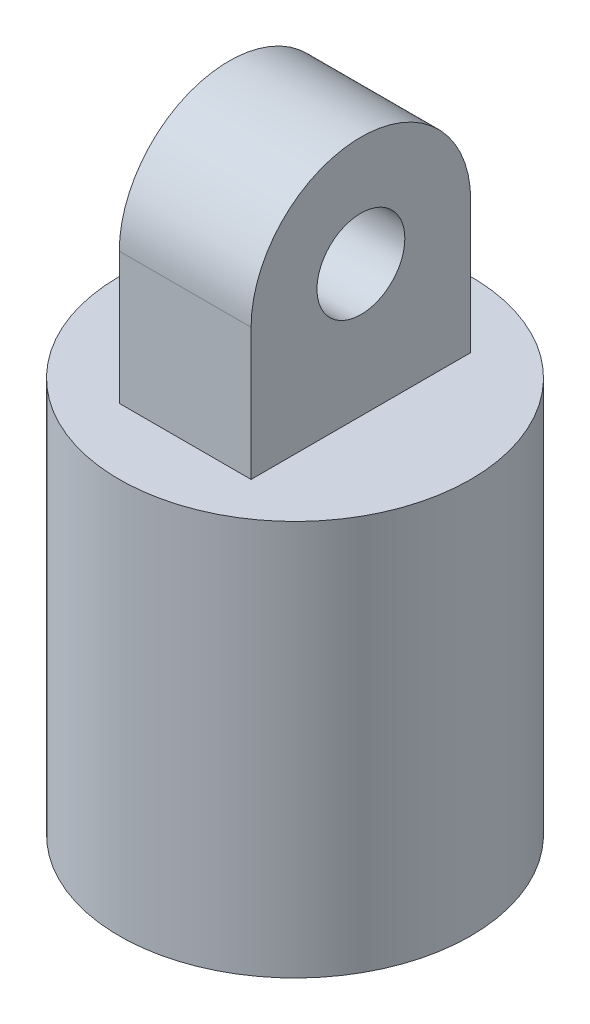
SolidWorks part; units mm, degrees
material "AISI 1020"
ref_plane "Front Plane" through (0, 0, 0) normal (0, 0, 1) x (1, 0, 0)
ref_plane "Top Plane" through (0, 0, 0) normal (0, 1, 0) x (1, 0, 0)
ref_plane "Right Plane" through (0, 0, 0) normal (1, 0, 0) x (0, 0, -1)
sketch "Sketch1" plane through (0, 0, 0) normal (0, 0, 1) x (1, 0, 0)
  line L0 (0, 0) -> (40, 0)
  line L1 (40, 0) -> (40, -90)
  line L2 (40, -90) -> (30, -90)
  line L3 (30, -90) -> (30, -10)
  line L4 (30, -10) -> (0, -10)
  line L5 (0, -10) -> (0, 0)
  line L6 (0, -10) -> (0, -90) construction
  line L7 (0, -90) -> (30, -90) construction
  dimension "D1" = 10
  dimension "D2" = 10
  dimension "D3" = 90
  dimension "D4" = 60
revolve "Revolve1" add sketch "Sketch1" angle 360 about L6
sketch "Sketch2" plane through (0, 0, 0) normal (1, 0, 0) x (0, 0, -1)
  line L0 (-25, 30) -> (-25, 0)
  line L1 (40, 0) -> (-40, 0) construction
  line L2 (-25, 0) -> (25, 0)
  line L3 (25, 0) -> (25, 30)
  arc A0 (25, 30) -> (-25, 30) centre (0, 30) ccw
  circle A1 centre (0, 30) radius 10
  dimension "D1" = 20
  dimension "D3" = 30
  dimension "D2" = 50
extrude "Boss-Extrude1" add sketch "Sketch2" along normal mid plane 30
equation "\"A\"= 100"
equation "\"B\"= 100"
equation "\"C\"= 100"
equation "\"D\"= 100"
equation "\"E\"= 100"
